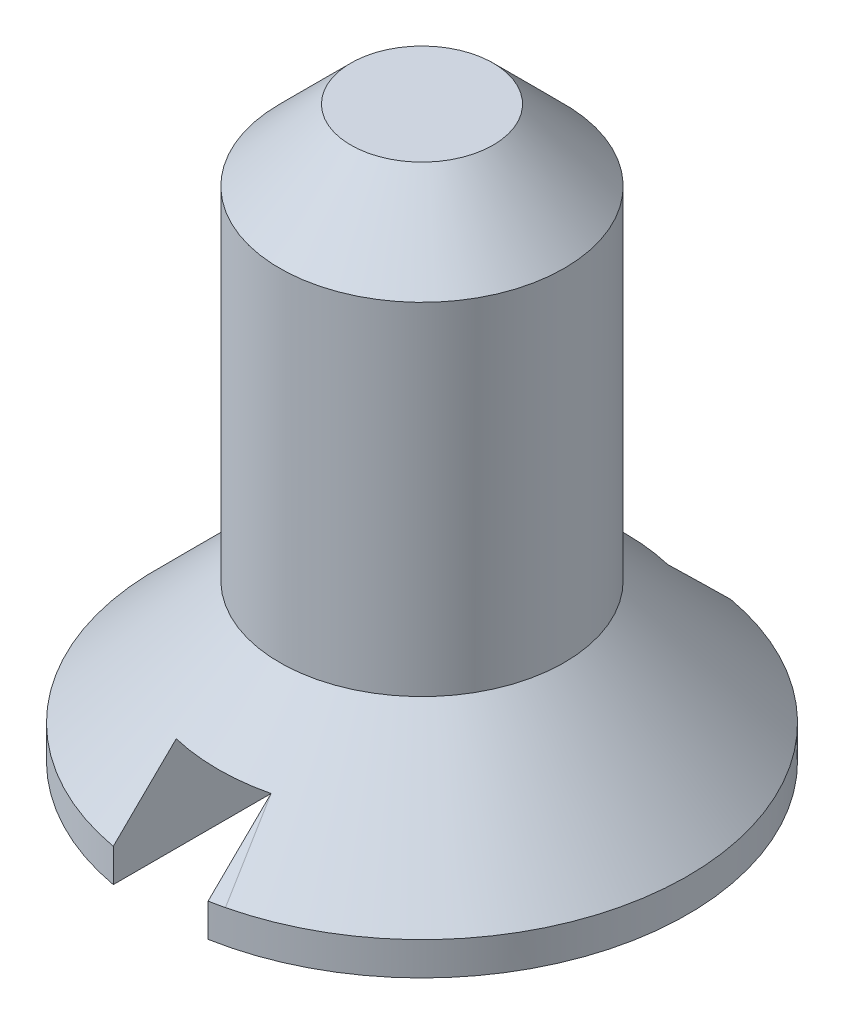
SolidWorks part; units mm, degrees
ref_plane "Спереди" through (0, 0, 0) normal (0, 0, 1) x (1, 0, 0)
ref_plane "Сверху" through (0, 0, 0) normal (0, 1, 0) x (1, 0, 0)
ref_plane "Справа" through (0, 0, 0) normal (1, 0, 0) x (0, 0, -1)
sketch "Эскиз1" plane through (0, 0, 0) normal (0, 0, 1) x (1, 0, 0)
  line L0 (0, 0) -> (-2.8, 0)
  line L1 (-2.8, 0) -> (-2.8, 0.35)
  line L2 (-2.8, 0.35) -> (-1.5, 1.65)
  line L3 (-1.5, 1.65) -> (-1.5, 6)
  line L4 (-1.5, 6) -> (0, 6)
  line L5 (0, 6) -> (0, 0)
  line L6 (-1.5, 1.65) -> (0, 1.65) construction
  line L7 (0, 0) -> (2.8, 0) construction
  dimension "D1" = 6
  dimension "D2" = 5.6
  dimension "D3" = 1.5
  dimension "D4" = 45
  dimension "D5" = 1.65
revolve "Повернуть1" add sketch "Эскиз1" angle 360 about L5
sketch "Эскиз2" plane through (0, 0, 0) normal (0, 0, 1) x (1, 0, 0)
  line L0 (-2.8, 0) -> (2.8, 0) construction
  line L1 (-0.5, 0) -> (0.5, 0)
  line L2 (-0.5, 0) -> (-0.5, 1)
  line L3 (-0.5, 1) -> (0.5, 1)
  line L4 (0.5, 0) -> (0.5, 1)
  dimension "D1" = 1
  dimension "D2" = 1
extrude "Вырез-Вытянуть1" cut sketch "Эскиз2" against normal mid plane 20
chamfer "Фаска1" distance 0.75 angle 45 1 edges at (-1.5, 6, 0)
